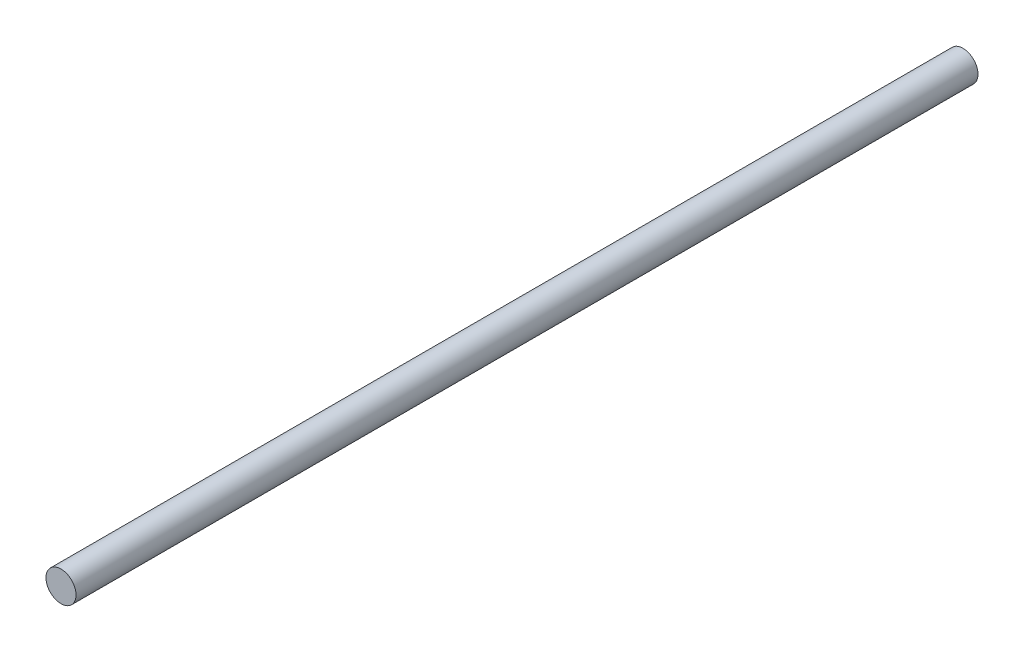
SolidWorks part; units mm, degrees
material "AISI 1020 Steel, Cold Rolled"
ref_plane "Front Plane" through (0, 0, 0) normal (0, 0, 1) x (1, 0, 0)
ref_plane "Top Plane" through (0, 0, 0) normal (0, 1, 0) x (1, 0, 0)
ref_plane "Right Plane" through (0, 0, 0) normal (1, 0, 0) x (0, 0, -1)
sketch "Sketch2" plane through (0, 0, 0) normal (0, 0, 1) x (1, 0, 0)
  circle A0 centre (0, 0) radius 25
  dimension "D1" = 50
extrude "Boss-Extrude1" add sketch "Sketch2" along normal blind 1500
